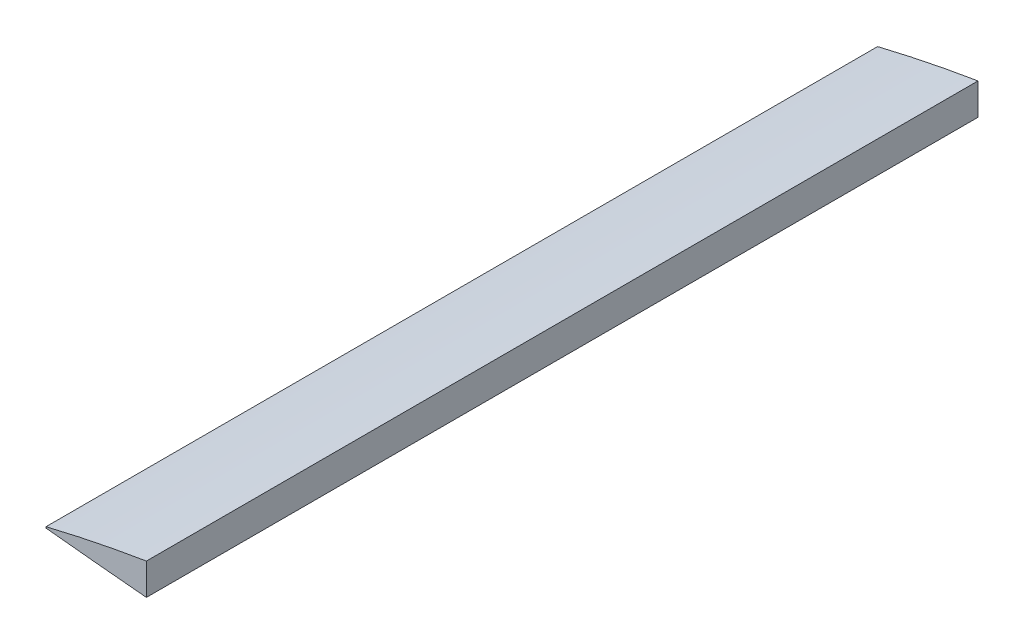
SolidWorks part; units mm, degrees
ref_plane "Front Plane" through (0, 0, 0) normal (0, 0, 1) x (1, 0, 0)
ref_plane "Top Plane" through (0, 0, 0) normal (0, 1, 0) x (1, 0, 0)
ref_plane "Right Plane" through (0, 0, 0) normal (1, 0, 0) x (0, 0, -1)
sketch "Sketch1" plane through (0, 0, 0) normal (0, 0, 1) x (1, 0, 0)
  line L0 (-210.2902, 15.5058) -> (-210.2902, -7.6848)
  line L1 (-284.176, 0.4539) -> (-284.176, -0.4466)
  spline S0 degree 3 poles (-210.2902, 15.5058) (-212.4482, 15.1479) (-217.6988, 14.2771) (-225.8551, 12.8241) (-234.5739, 11.2048) (-242.7164, 9.62) (-250.2347, 8.0968) (-257.084, 6.6572) (-263.2241, 5.3239) (-268.6191, 4.1181) (-273.2376, 3.0598) (-277.0529, 2.1669) (-280.0432, 1.4552) (-282.1913, 0.9372) (-283.4751, 0.6251) (-284.0416, 0.4867) (-284.176, 0.4539) knots 0 0 0 0 0.087007 0.211705 0.329527 0.439741 0.541661 0.634652 0.718135 0.791585 0.85454 0.906603 0.947445 0.976805 0.994497 1 1 1 1
  spline S1 degree 3 poles (-210.2902, -7.6848) (-212.1587, -7.5154) (-217.125, -7.0652) (-225.0196, -6.3317) (-233.7877, -5.5057) (-241.996, -4.7193) (-249.5923, -3.9801) (-256.5279, -3.2948) (-262.7581, -2.6701) (-268.2426, -2.1118) (-272.9458, -1.6282) (-276.8367, -1.2191) (-279.8905, -0.906) (-282.085, -0.6533) (-283.41, -0.5467) (-284.0076, -0.446) (-284.1661, -0.4466) (-284.176, -0.4466) knots 0 0 0 0 0.075811 0.201508 0.320388 0.431695 0.534719 0.628797 0.713321 0.78774 0.851567 0.90438 0.945827 0.975633 0.993597 0.999599 1 1 1 1
extrude "Boss-Extrude1" add sketch "Sketch1" against normal blind 612
ref_plane "Plane1" through (0, 0, -96.9) normal (0, 0, 1) x (1, 0, 0)
sketch "Sketch2" plane through (0, 0, -96.9) normal (0, 0, 1) x (1, 0, 0)
  line L0 (-233.632, -8.192) -> (-212.632, -8.192)
  line L1 (-212.632, -8.192) -> (-212.632, 3.308)
  line L2 (-212.632, 3.308) -> (-233.632, 3.308)
  line L3 (-233.632, 3.308) -> (-233.632, -8.192)
extrude "Cut-Extrude1" cut sketch "Sketch2" along normal blind 13
